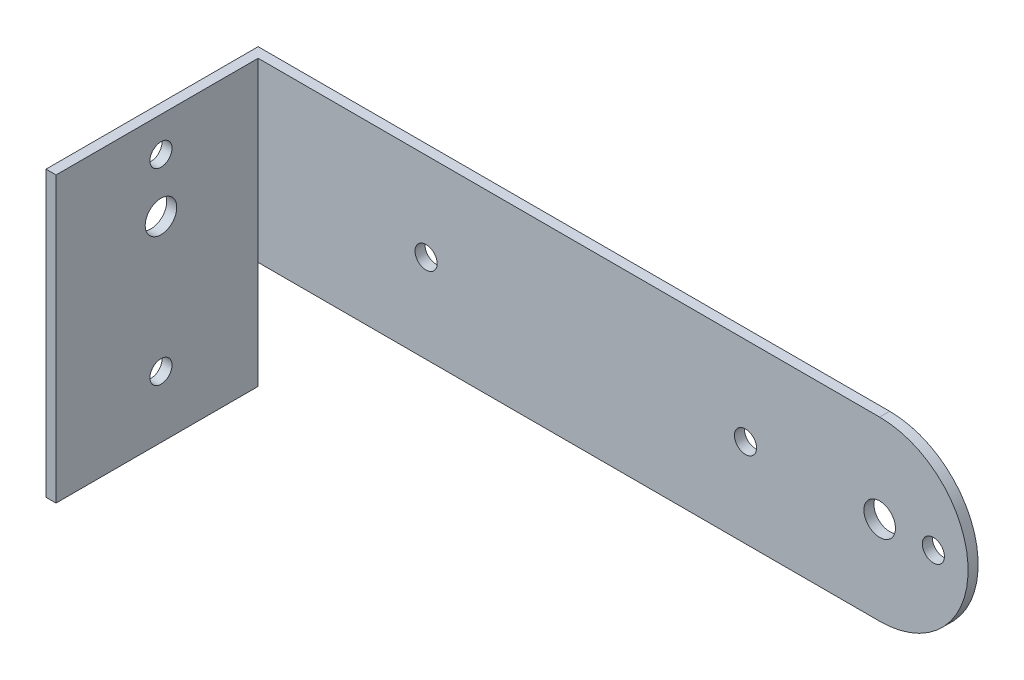
SolidWorks part; units mm, degrees
material "6061 Alloy"
ref_plane "Front Plane" through (0, 0, 0) normal (0, 0, 1) x (1, 0, 0)
ref_plane "Top Plane" through (0, 0, 0) normal (0, 1, 0) x (1, 0, 0)
ref_plane "Right Plane" through (0, 0, 0) normal (1, 0, 0) x (0, 0, -1)
sketch "Sketch1" plane through (0, 0, 0) normal (0, 0, 1) x (1, 0, 0)
  line L0 (0, 14) -> (-100, 14)
  line L1 (-100, 14) -> (-100, -14)
  line L2 (-100, -14) -> (0, -14)
  arc A0 (0, -14) -> (0, 14) centre (0, 0) ccw
  dimension "D1" = 14
  dimension "D2" = 100
extrude "Boss-Extrude1" add sketch "Sketch1" along normal blind 1.59
sketch "Sketch2" plane through (0, 0, 1.59) normal (0, 0, 1) x (1, 0, 0)
  line L1 (-100, 14) -> (-98.41, 14)
  line L2 (-100, 14) -> (-100, -31)
  line L3 (-100, -31) -> (-98.41, -31)
  line L4 (-98.41, 14) -> (-98.41, -31)
  point P5 (-98.41, -8.5)
  dimension "D1" = 45
  dimension "D2" = 1.59
extrude "Boss-Extrude2" add sketch "Sketch2" along normal blind 32
sketch "Sketch3" plane through (0, 0, 1.59) normal (0, 0, 1) x (1, 0, 0)
  line L0 (14, 0) -> (-148.456, 0) construction
  line L1 (-98.41, -14) -> (-98.41, 14) construction
  arc A0 (0, -14) -> (0, 14) centre (0, 0) ccw construction
  circle A1 centre (0, 0) radius 2.5
  circle A2 centre (8.5, 0) radius 1.75
  circle A3 centre (-21.25, 0) radius 1.75
  circle A6 centre (-71.82, 0) radius 1.75
  dimension "D6" = 5
  dimension "D7" = 26.59
  dimension "D1" = 3.5
  dimension "D2" = 3.5
  dimension "D3" = 8.5
  dimension "D4" = 29.75
extrude "Cut-Extrude1" cut sketch "Sketch3" against normal through all
sketch "Sketch4" plane through (-100, 0, 0) normal (-1, 0, 0) x (0, 0, 1)
  line L0 (16.975, 19.3535) -> (16.975, -38.9502) construction
  line L1 (0, 14) -> (0, -14) construction
  circle A0 centre (16.975, 0) radius 2.5
  circle A1 centre (16.975, 8.5) radius 1.75
  circle A2 centre (16.975, -21.25) radius 1.75
  dimension "D4" = 5
  dimension "D5" = 3.5
  dimension "D6" = 3.5
  dimension "D1" = 16.975
  dimension "D2" = 8.5
  dimension "D3" = 29.75
extrude "Cut-Extrude2" cut sketch "Sketch4" against normal through all
